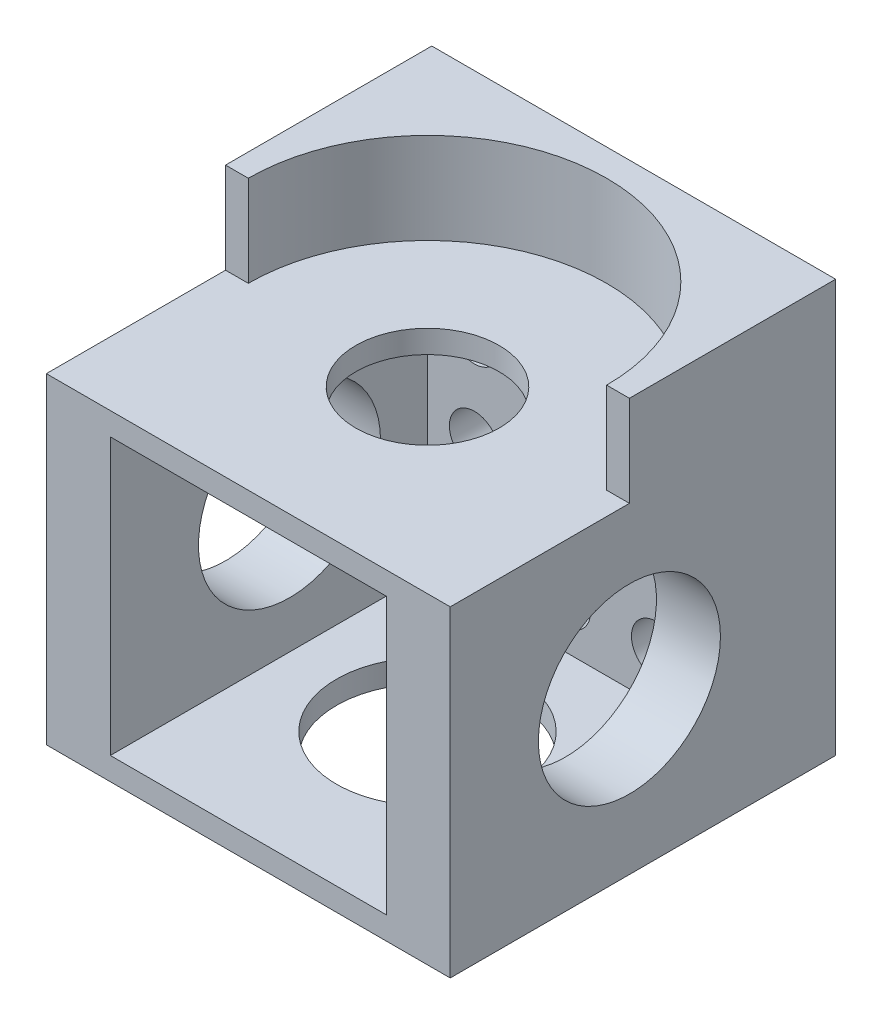
SolidWorks part; units mm, degrees
ref_plane "Front Plane" through (0, 0, 0) normal (0, 0, 1) x (1, 0, 0)
ref_plane "Top Plane" through (0, 0, 0) normal (0, 1, 0) x (1, 0, 0)
ref_plane "Right Plane" through (0, 0, 0) normal (1, 0, 0) x (0, 0, -1)
sketch "Sketch1" plane through (0, 0, 0) normal (0, 1, 0) x (1, 0, 0)
  line L1 (-19.25, -19.25) -> (19.25, -19.25)
  line L2 (-19.25, -19.25) -> (-19.25, 19.25)
  line L3 (-19.25, 19.25) -> (19.25, 19.25)
  line L4 (19.25, -19.25) -> (19.25, 19.25)
  line L5 (-19.25, -19.25) -> (19.25, 19.25) construction
  line L6 (-19.25, 19.25) -> (19.25, -19.25) construction
  line L7 (-22.425, -22.425) -> (22.425, -22.425)
  line L8 (-22.425, -22.425) -> (-22.425, 22.425)
  line L9 (-22.425, 22.425) -> (22.425, 22.425)
  line L10 (22.425, -22.425) -> (22.425, 22.425)
  line L11 (-22.425, -22.425) -> (22.425, 22.425) construction
  line L12 (-22.425, 22.425) -> (22.425, -22.425) construction
  point P0 (0, 0)
  point P6 (0, 0)
  dimension "D1" = 38.5
  dimension "D2" = 38.5
  dimension "D3" = 3.175
  dimension "D4" = 3.175
extrude "Boss-Extrude1" add sketch "Sketch1" along normal mid plane 38.5
sketch "Sketch2" plane through (0, 19.25, 0) normal (0, 1, 0) x (1, 0, 0)
  line L1 (-22.425, 22.425) -> (22.425, 22.425)
  line L2 (-22.425, 22.425) -> (-22.425, -22.425)
  line L3 (-22.425, -22.425) -> (22.425, -22.425)
  line L4 (22.425, 22.425) -> (22.425, -22.425)
extrude "Boss-Extrude2" add sketch "Sketch2" along normal blind 3.175
sketch "Sketch3" plane through (0, -19.25, 0) normal (0, -1, 0) x (1, 0, 0)
  line L1 (22.425, -22.425) -> (-22.425, -22.425)
  line L2 (22.425, -22.425) -> (22.425, 22.425)
  line L3 (22.425, 22.425) -> (-22.425, 22.425)
  line L4 (-22.425, -22.425) -> (-22.425, 22.425)
extrude "Boss-Extrude3" add sketch "Sketch3" along normal blind 3.175
sketch "Sketch5" plane through (0, -22.425, -22.425) normal (0, 1, 0) x (1, 0, 0)
  circle A0 centre (0, -22.425) radius 12.7
  dimension "D1" = 25.4
extrude "Cut-Extrude1" cut sketch "Sketch5" along normal up to next (3.175 mm away) from surface at 0 starting at face at (0, -22.425, 0)
sketch "Sketch6" plane through (0, 0, 0) normal (0, 1, 0) x (1, 0, 0)
  circle A0 centre (0, 0) radius 10
  dimension "D1" = 20
extrude "Cut-Extrude2" cut sketch "Sketch6" against normal up to next (19.25 mm away) from surface at 22.425 starting at face at (0, 22.425, 0)
sketch "Sketch8" plane through (0, 0, -22.425) normal (0, 0, -1) x (-1, 0, 0)
  line L0 (-12.7, 12.7) -> (0, 12.7) construction
  line L1 (-22.425, -22.425) -> (22.425, -22.425)
  line L2 (-22.425, 22.425) -> (-22.425, -22.425)
  line L3 (-22.425, 22.425) -> (22.425, 22.425)
  line L4 (22.425, -22.425) -> (22.425, 22.425)
  circle A0 centre (-12.7, 12.7) radius 2.2225
  circle A1 centre (0, 12.7) radius 2.2225
  circle A2 centre (12.7, 12.7) radius 2.2225
  circle A3 centre (0, 0) radius 2.2225
  circle A4 centre (12.7, 0) radius 2.2225
  circle A5 centre (0, -12.7) radius 2.2225
  circle A6 centre (12.7, -12.7) radius 2.2225
  circle A7 centre (-12.7, 0) radius 2.2225
  circle A8 centre (-12.7, -12.7) radius 2.2225
  dimension "D1" = 4.445
  dimension "D2" = 12.7
  dimension "D3" = 12.7
  dimension "D6" = 12.7
  dimension "D4" = 3
  dimension "D5" = 3
extrude "Boss-Extrude4" add sketch "Sketch8" along normal blind 6.35
sketch "Sketch9" plane through (0, 0, -19.25) normal (0, 0, 1) x (1, 0, 0)
  line L0 (12.7, 12.7) -> (0, 12.7) construction
  circle A0 centre (12.7, 12.7) radius 3.4925
  circle A1 centre (0, 12.7) radius 3.4925
  circle A2 centre (-12.7, 12.7) radius 3.4925
  circle A3 centre (0, 0) radius 3.4925
  circle A4 centre (-12.7, 0) radius 3.4925
  circle A5 centre (0, -12.7) radius 3.4925
  circle A6 centre (-12.7, -12.7) radius 3.4925
  circle A7 centre (12.7, 0) radius 3.4925
  circle A8 centre (12.7, -12.7) radius 3.4925
  dimension "D1" = 6.985
  dimension "D4" = 12.7
  dimension "D2" = 3
  dimension "D3" = 3
extrude "Cut-Extrude4" cut sketch "Sketch9" against normal blind 6.35
sketch "Sketch10" plane through (0, 0, 22.425) normal (0, 0, 1) x (1, 0, 0)
  line L0 (-22.425, 22.425) -> (-22.425, -22.425) construction
  line L1 (-19.25, -19.25) -> (19.25, -19.25)
  line L2 (-19.25, -19.25) -> (-19.25, 19.25)
  line L3 (-19.25, 19.25) -> (19.25, 19.25)
  line L4 (19.25, -19.25) -> (19.25, 19.25)
  line L5 (-19.25, -19.25) -> (19.25, 19.25) construction
  line L6 (-19.25, 19.25) -> (19.25, -19.25) construction
  line L7 (-22.425, 22.425) -> (22.425, 22.425) construction
  point P0 (0, 0)
  dimension "D1" = 3.175
  dimension "D2" = 3.175
extrude "Cut-Extrude5" cut sketch "Sketch10" against normal up to next
sketch "Sketch11" plane through (0, 22.425, 0) normal (0, 1, 0) x (1, 0, 0)
  line L0 (-28.175, 0) -> (-25, 0)
  line L1 (28.175, 0) -> (25, 0)
  line L2 (-28.175, 0) -> (-28.175, 28.775)
  line L3 (-28.175, 28.775) -> (28.175, 28.775)
  line L4 (28.175, 0) -> (28.175, 28.775)
  line L5 (-22.425, 28.775) -> (22.425, 28.775) construction
  arc A0 (25, 0) -> (-25, 0) centre (0, 0) ccw
  point P13 (-28.175, 0)
  point P14 (28.175, 0)
  dimension "D1" = 50
  dimension "D3" = 3.175
  dimension "D4" = 3.175
extrude "Boss-Extrude5" add sketch "Sketch11" along normal blind 12.7
sketch "Sketch12" plane through (-22.425, 0, 0) normal (-1, 0, 0) x (0, 0, 1)
  line L7 (-11.0508, 22.425) -> (-28.775, 22.425)
  line L8 (-28.775, 22.425) -> (-28.775, -22.425)
  line L9 (-28.775, -22.425) -> (22.425, -22.425)
  line L10 (22.425, -22.425) -> (22.425, 22.425)
  line L11 (22.425, 22.425) -> (-11.0508, 22.425)
  line L14 (-11.0508, 22.425) -> (-28.775, 22.425)
  line L15 (-28.775, 22.425) -> (-28.775, -22.425)
  line L16 (-28.775, -22.425) -> (22.425, -22.425)
  line L17 (22.425, -22.425) -> (22.425, 22.425)
  line L18 (22.425, 22.425) -> (-11.0508, 22.425)
  dimension "D1" = 0
extrude "Boss-Extrude6" add sketch "Sketch12" along normal up to surface (5.75 mm away) up to face at (-28.175, 28.775, -14.3875)
sketch "Sketch13" plane through (22.425, 0, 0) normal (1, 0, 0) x (0, 0, -1)
  line L7 (-22.425, 22.425) -> (-22.425, -22.425)
  line L8 (-22.425, -22.425) -> (28.775, -22.425)
  line L9 (28.775, -22.425) -> (28.775, 22.425)
  line L10 (28.775, 22.425) -> (11.0508, 22.425)
  line L11 (11.0508, 22.425) -> (-22.425, 22.425)
  line L14 (-22.425, 22.425) -> (-22.425, -22.425)
  line L15 (-22.425, -22.425) -> (28.775, -22.425)
  line L16 (28.775, -22.425) -> (28.775, 22.425)
  line L17 (28.775, 22.425) -> (11.0508, 22.425)
  line L18 (11.0508, 22.425) -> (-22.425, 22.425)
  dimension "D1" = 0
extrude "Boss-Extrude7" add sketch "Sketch13" along normal up to surface (5.75 mm away) up to face at (28.175, 28.775, -14.3875)
sketch "Sketch15" plane through (0, 0, 22.425) normal (0, 0, 1) x (1, 0, 0)
  line L1 (-19.25, 19.25) -> (19.25, 19.25)
  line L2 (-19.25, 19.25) -> (-19.25, -19.25)
  line L3 (-19.25, -19.25) -> (19.25, -19.25)
  line L4 (19.25, 19.25) -> (19.25, -19.25)
  line L8 (28.175, 22.425) -> (-28.175, 22.425)
  line L9 (-28.175, 22.425) -> (-28.175, -22.425)
  line L10 (-28.175, -22.425) -> (28.175, -22.425)
  line L11 (28.175, -22.425) -> (28.175, 22.425)
  line L16 (28.175, 22.425) -> (-28.175, 22.425)
  line L17 (-28.175, 22.425) -> (-28.175, -22.425)
  line L18 (-28.175, -22.425) -> (28.175, -22.425)
  line L19 (28.175, -22.425) -> (28.175, 22.425)
  dimension "D1" = 0
extrude "Boss-Extrude8" add sketch "Sketch15" along normal offset from surface (2.575 mm away) 25 up to plane "Front Plane"
sketch "Sketch7" plane through (0, 0, 0) normal (-1, 0, 0) x (0, 0, 1)
  circle A0 centre (0, 0) radius 12.7
  dimension "D1" = 25.4
extrude "Cut-Extrude3" cut sketch "Sketch7" against normal through all both and the other way through all from surface at 0 starting at plane "Right Plane"
